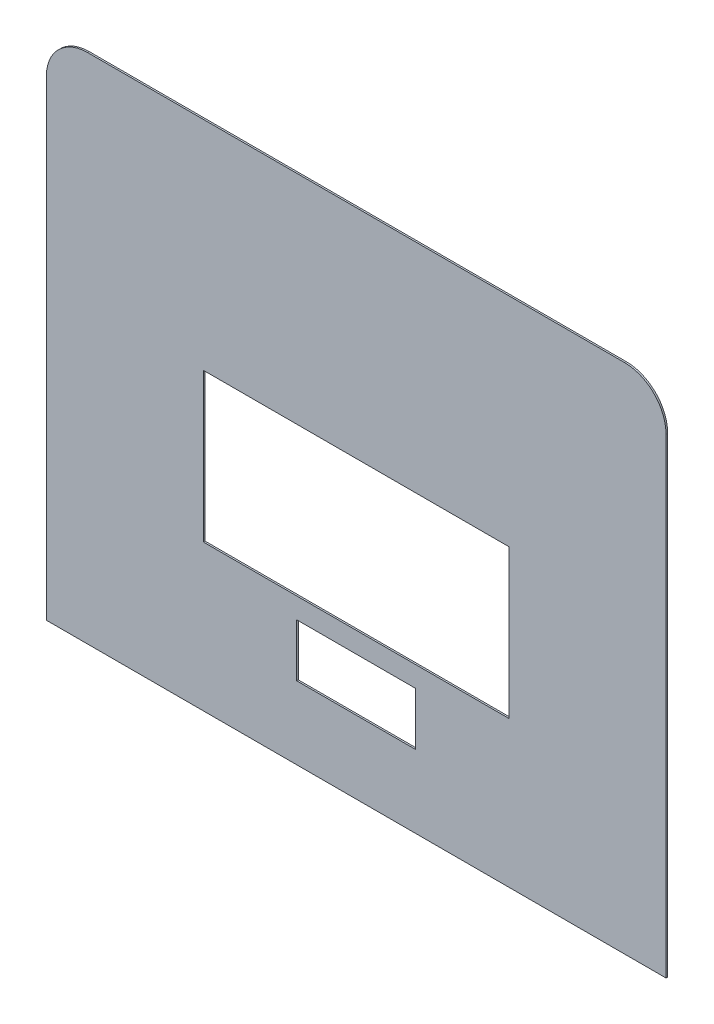
SolidWorks part; units mm, degrees
material "Plain Carbon Steel"
ref_plane "Front Plane" through (0, 0, 0) normal (0, 0, 1) x (1, 0, 0)
ref_plane "Top Plane" through (0, 0, 0) normal (0, 1, 0) x (1, 0, 0)
ref_plane "Right Plane" through (0, 0, 0) normal (1, 0, 0) x (0, 0, -1)
sketch "Sketch1" plane through (0, 0, 0) normal (0, 0, 1) x (1, 0, 0)
  line L0 (0, 310) -> (0, -310) construction
  line L1 (-325, 310) -> (325, 310)
  line L2 (-375, 260) -> (-375, -310)
  line L3 (-375, -310) -> (375, -310)
  line L4 (375, 260) -> (375, -310)
  line L5 (-375, 310) -> (375, -310) construction
  line L6 (-375, -310) -> (375, 310) construction
  line L8 (-72, -158) -> (72, -158)
  line L9 (-72, -158) -> (-72, -222)
  line L10 (-72, -222) -> (72, -222)
  line L11 (72, -158) -> (72, -222)
  line L12 (-72, -158) -> (72, -222) construction
  line L13 (-72, -222) -> (72, -158) construction
  line L14 (-185, 47) -> (185, 47)
  line L15 (-185, 47) -> (-185, -133)
  line L16 (-185, -133) -> (185, -133)
  line L17 (185, 47) -> (185, -133)
  line L18 (-185, 47) -> (185, -133) construction
  line L19 (-185, -133) -> (185, 47) construction
  arc A0 (325, 310) -> (375, 260) centre (325, 260) cw
  arc A1 (-325, 310) -> (-375, 260) centre (-325, 260) ccw
  point P0 (0, 0)
  point P14 (0, -190)
  point P19 (0, -43)
  dimension "D3" = 50
  dimension "D1" = 750
  dimension "D2" = 620
  dimension "D4" = 64
  dimension "D5" = 88
  dimension "D6" = 144
  dimension "D7" = 180
  dimension "D8" = 370
  dimension "D9" = 177
extrude "Boss-Extrude1" add sketch "Sketch1" along normal mid plane 2
